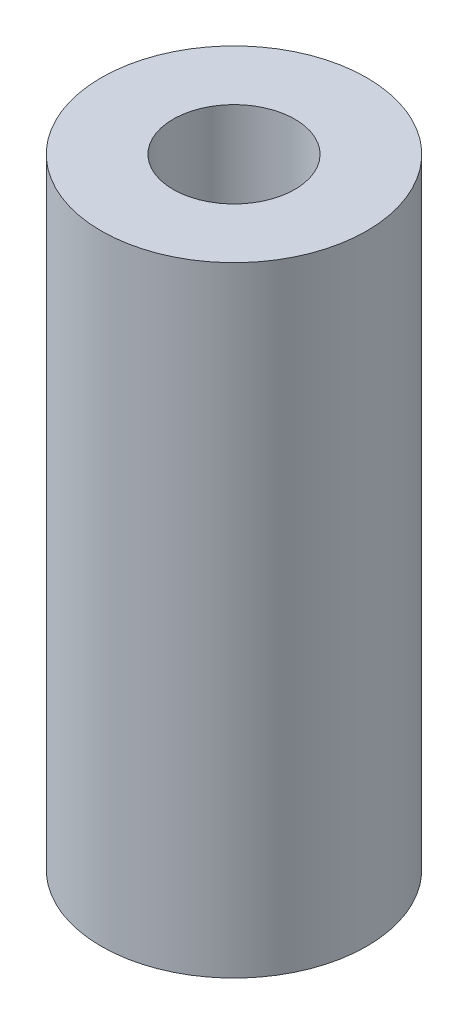
SolidWorks part; units mm, degrees
ref_plane "Front Plane" through (0, 0, 0) normal (0, 0, 1) x (1, 0, 0)
ref_plane "Top Plane" through (0, 0, 0) normal (0, 1, 0) x (1, 0, 0)
ref_plane "Right Plane" through (0, 0, 0) normal (1, 0, 0) x (0, 0, -1)
sketch "Sketch1" plane through (0, 0, 0) normal (0, 1, 0) x (1, 0, 0)
  circle A0 centre (0, 0) radius 2.1844
  circle A1 centre (0, 0) radius 4.7625
  dimension "D1" = 4.3688
  dimension "D2" = 9.525
extrude "Boss-Extrude1" add sketch "Sketch1" along normal blind 22.225
